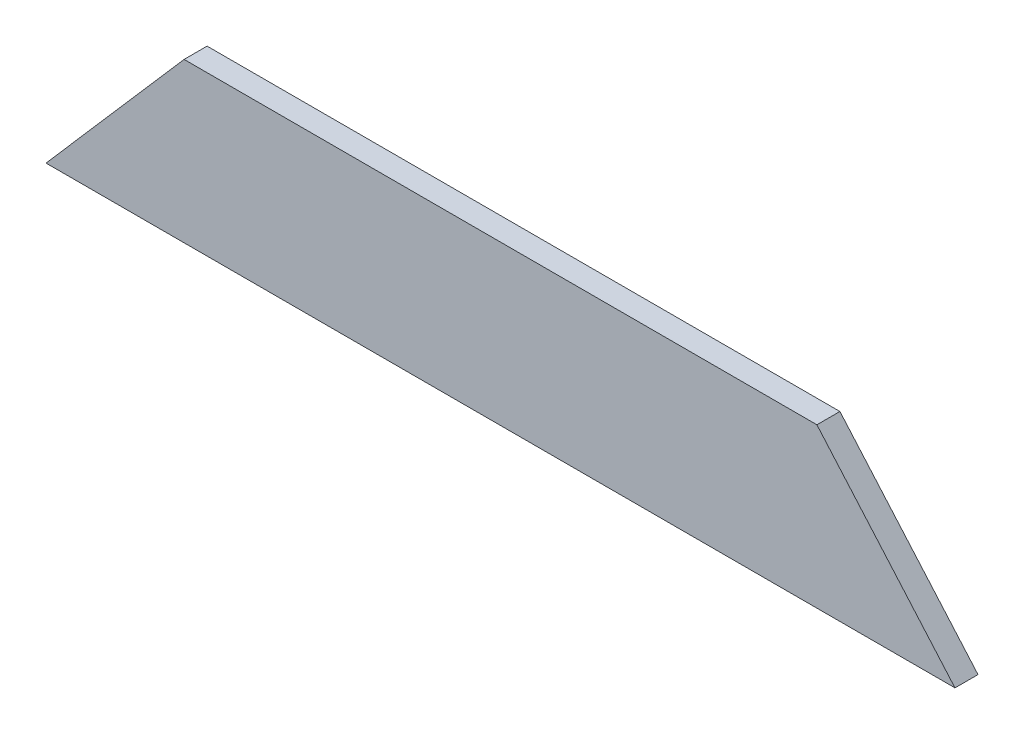
SolidWorks part; units mm, degrees
ref_plane "Ön Düzlem" through (0, 0, 0) normal (0, 0, 1) x (1, 0, 0)
ref_plane "Üst Düzlem" through (0, 0, 0) normal (0, 1, 0) x (1, 0, 0)
ref_plane "Sağ Düzlem" through (0, 0, 0) normal (1, 0, 0) x (0, 0, -1)
sketch "Çizim2" plane through (0, 0, 0) normal (0, 0, 1) x (1, 0, 0)
  line L0 (0, 0) -> (79, 0)
  line L1 (79, 0) -> (67, 13.8044)
  line L2 (67, 13.8044) -> (12, 13.8044)
  line L3 (12, 13.8044) -> (0, 0)
  dimension "D1" = 55
  dimension "D2" = 12
  dimension "D3" = 49
extrude "Yükseklik-Ekstrüzyon1" add sketch "Çizim2" along normal blind 2
